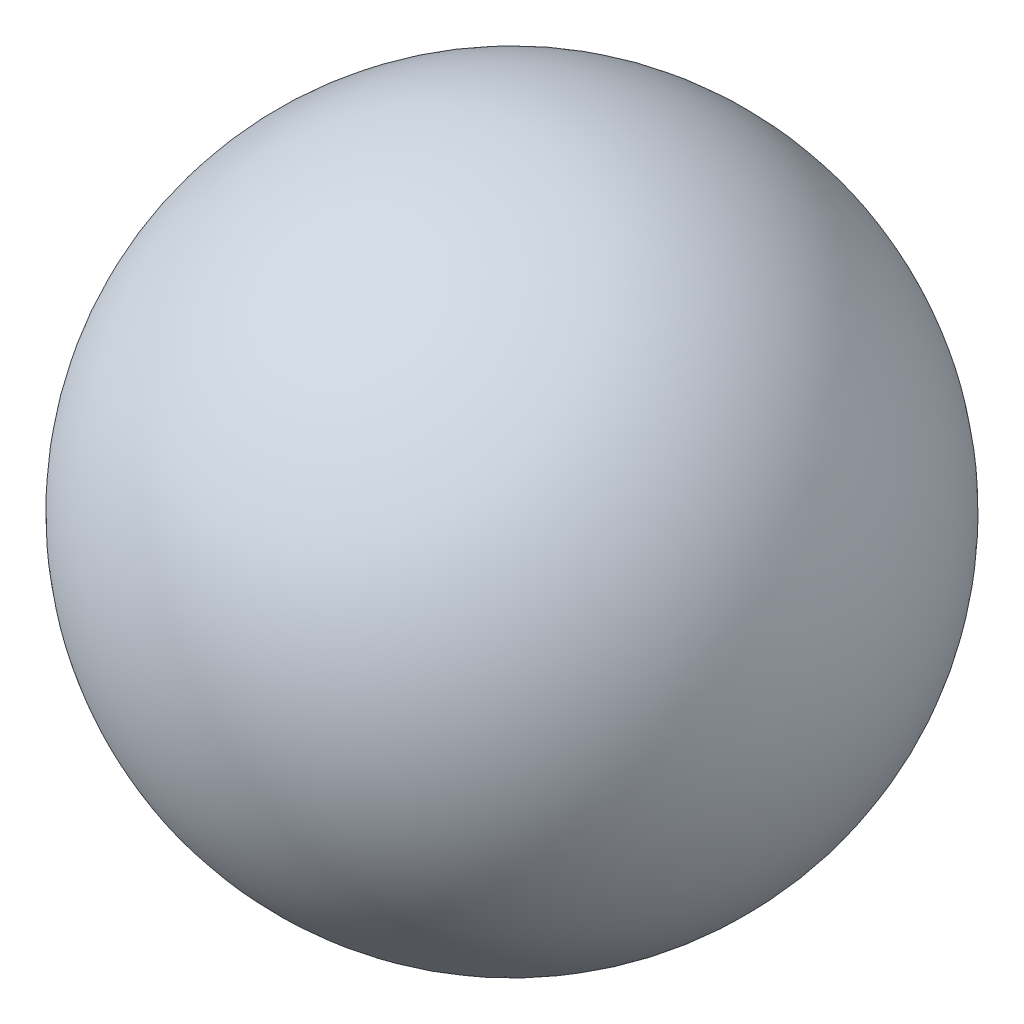
SolidWorks part; units mm, degrees
ref_plane "Front Plane" through (0, 0, 0) normal (0, 0, 1) x (1, 0, 0)
ref_plane "Top Plane" through (0, 0, 0) normal (0, 1, 0) x (1, 0, 0)
ref_plane "Right Plane" through (0, 0, 0) normal (1, 0, 0) x (0, 0, -1)
sketch "Sketch1" plane through (0, 0, 0) normal (0, 1, 0) x (1, 0, 0)
  line L0 (0, 15) -> (0, -15)
  arc A0 (0, 15) -> (0, -15) centre (0, 0) ccw
  dimension "D1" = 15
revolve "Revolve1" add sketch "Sketch1" angle 360 about L0
